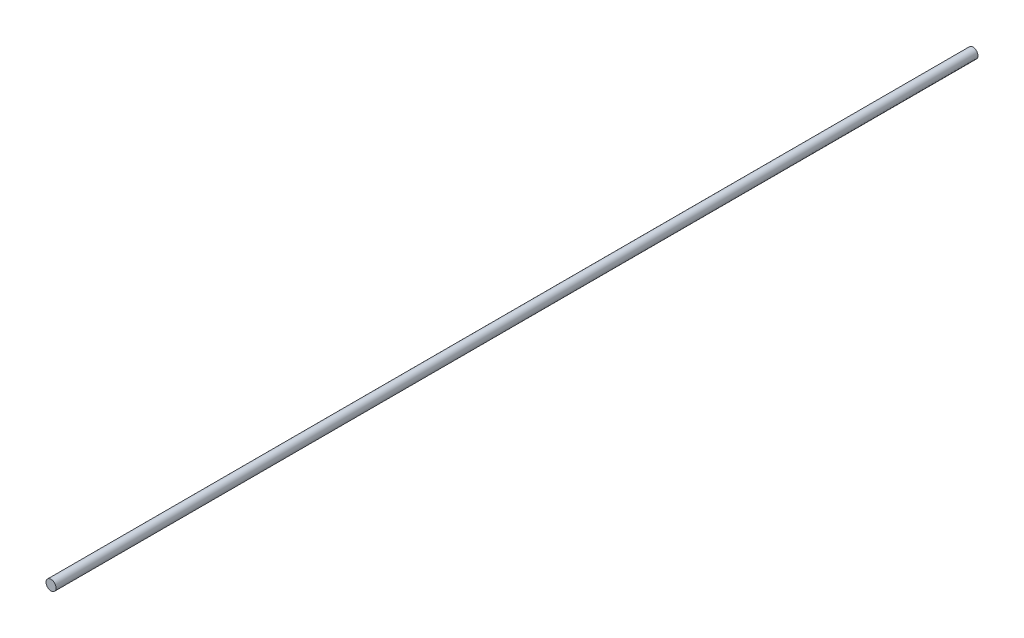
SolidWorks part; units mm, degrees
ref_plane "Front Plane" through (0, 0, 0) normal (0, 0, 1) x (1, 0, 0)
ref_plane "Top Plane" through (0, 0, 0) normal (0, 1, 0) x (1, 0, 0)
ref_plane "Right Plane" through (0, 0, 0) normal (1, 0, 0) x (0, 0, -1)
sketch "Sketch1" plane through (0, 0, 0) normal (0, 0, 1) x (1, 0, 0)
  circle A0 centre (0, 0) radius 6.1
extrude "Boss-Extrude1" add sketch "Sketch1" along normal mid plane 1120
